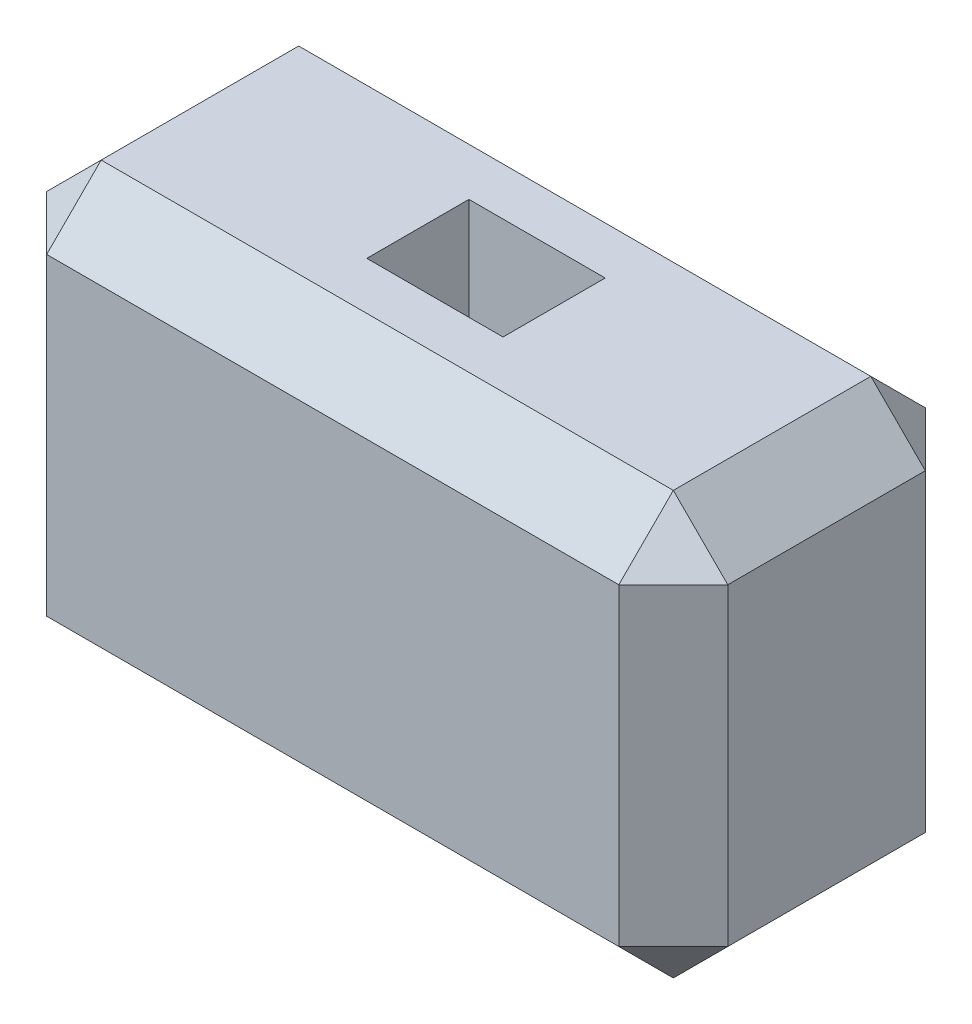
SolidWorks part; units mm, degrees
ref_plane "Front Plane" through (0, 0, 0) normal (0, 0, 1) x (1, 0, 0)
ref_plane "Top Plane" through (0, 0, 0) normal (0, 1, 0) x (1, 0, 0)
ref_plane "Right Plane" through (0, 0, 0) normal (1, 0, 0) x (0, 0, -1)
sketch "Sketch1" plane through (0, 0, 0) normal (0, 0, 1) x (1, 0, 0)
  line L1 (-63.5, -39.37) -> (63.5, -39.37)
  line L2 (-63.5, -39.37) -> (-63.5, 39.37)
  line L3 (-63.5, 39.37) -> (63.5, 39.37)
  line L4 (63.5, -39.37) -> (63.5, 39.37)
  line L5 (-63.5, -39.37) -> (63.5, 39.37) construction
  line L6 (-63.5, 39.37) -> (63.5, -39.37) construction
  point P0 (0, 0)
  dimension "D1" = 78.74
  dimension "D2" = 127
extrude "Boss-Extrude1" add sketch "Sketch1" along normal blind 19.05
sketch "Sketch2" plane through (0, 0, 19.05) normal (0, 0, 1) x (1, 0, 0)
  line L0 (-63.5, -39.37) -> (63.5, -39.37) construction
  line L1 (-63.5, 39.37) -> (-12.7, 39.37)
  line L2 (-63.5, 39.37) -> (-63.5, -39.37)
  line L3 (-63.5, -39.37) -> (-12.7, -39.37)
  line L4 (-12.7, 39.37) -> (-12.7, -39.37)
  line L6 (63.5, 39.37) -> (12.7, 39.37)
  line L7 (63.5, 39.37) -> (63.5, -39.37)
  line L8 (63.5, -39.37) -> (12.7, -39.37)
  line L9 (12.7, 39.37) -> (12.7, -39.37)
  dimension "D1" = 25.4
extrude "Boss-Extrude2" add sketch "Sketch2" along normal blind 19.05
sketch "Sketch3" plane through (0, 0, 38.1) normal (0, 0, 1) x (1, 0, 0)
  line L0 (12.7, -39.37) -> (63.5, -39.37) construction
  line L1 (-63.5, 39.37) -> (63.5, 39.37)
  line L2 (-63.5, 39.37) -> (-63.5, -39.37)
  line L3 (-63.5, -39.37) -> (63.5, -39.37)
  line L4 (63.5, 39.37) -> (63.5, -39.37)
  line L5 (63.5, -39.37) -> (63.5, 39.37) construction
extrude "Boss-Extrude3" add sketch "Sketch3" along normal blind 19.05
chamfer "Chamfer1" distance 10.16 angle 45 12 edges at (0, 39.37, 0) (0, -39.37, 0) (0, 39.37, 57.15) (63.5, -39.37, 28.575) (63.5, 0, 0) (63.5, 39.37, 28.575) (63.5, 0, 57.15) (0, -39.37, 57.15) (-63.5, 39.37, 28.575) (-63.5, 0, 57.15) (-63.5, -39.37, 28.575) (-63.5, 0, 0)
